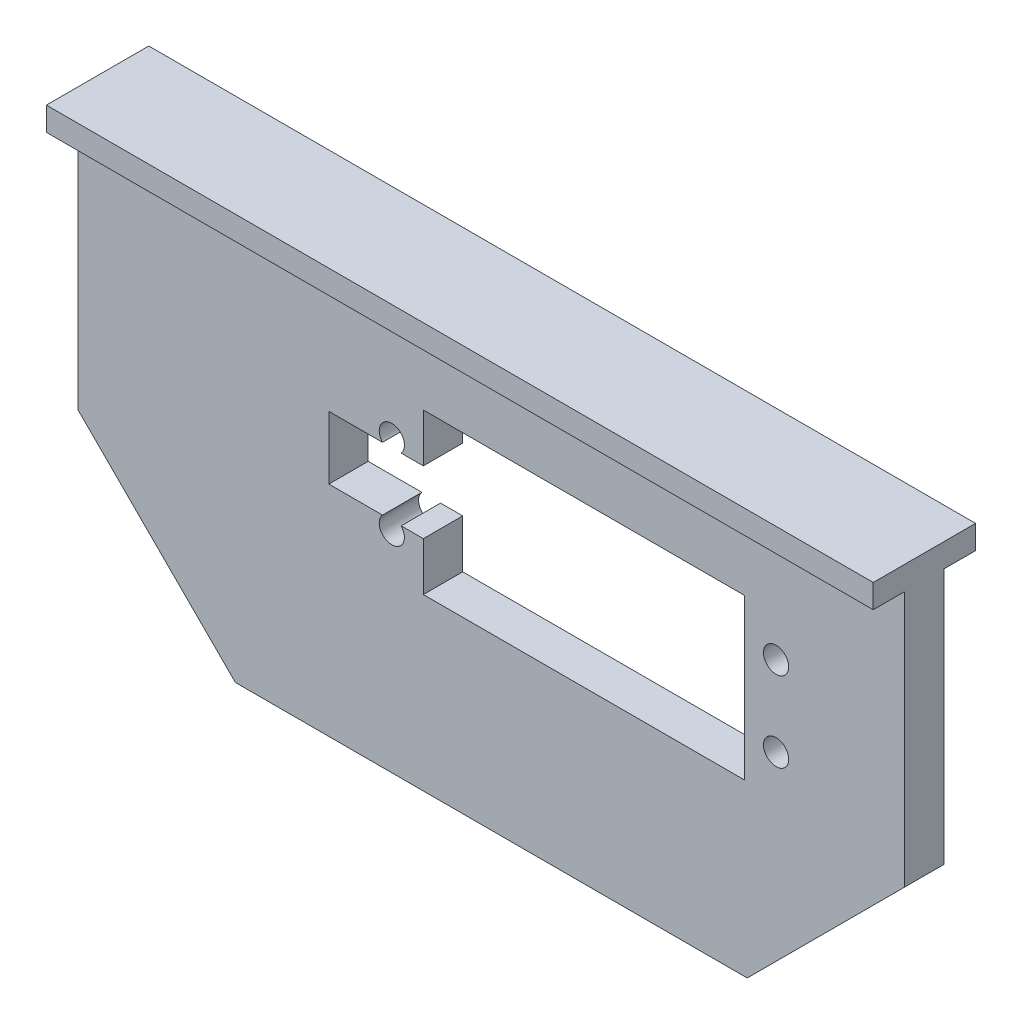
SolidWorks part; units mm, degrees
ref_plane "前视基准面" through (0, 0, 0) normal (0, 0, 1) x (1, 0, 0)
ref_plane "上视基准面" through (0, 0, 0) normal (0, 1, 0) x (1, 0, 0)
ref_plane "右视基准面" through (0, 0, 0) normal (1, 0, 0) x (0, 0, -1)
other "Configuration Table"
sketch "草图1" plane through (0, 0, 0) normal (0, 0, 1) x (1, 0, 0)
  line L2 (43.865, -10.5968) -> (84.665, -10.5968)
  line L3 (43.865, -10.5968) -> (43.865, -30.8968)
  line L4 (43.865, -30.8968) -> (84.665, -30.8968)
  line L5 (84.665, -10.5968) -> (84.665, -30.8968)
  line L6 (0, 0) -> (0, -52.5)
  line L7 (105, 0) -> (105, -52.5)
  line L8 (0, -52.5) -> (105, -52.5)
  line L9 (0, 0) -> (105, 0)
  circle A2 centre (39.865, -15.6718) radius 1.6
  circle A3 centre (39.865, -25.8218) radius 1.6
  circle A4 centre (88.665, -15.6718) radius 1.6
  circle A5 centre (88.665, -25.8218) radius 1.6
  dimension "D5" = 3.2
  dimension "D6" = 3.2
  dimension "D10" = 3.2
  dimension "D11" = 3.2
  dimension "D7" = 52.5
  dimension "D1" = 105
  dimension "D3" = 40.8
  dimension "D4" = 20.3
  dimension "D8" = 4
  dimension "D9" = 4
  dimension "D12" = 4
  dimension "D13" = 4
extrude "凸台-拉伸1" add sketch "草图1" along normal blind 5
sketch "草图3" plane through (0, 0, 0) normal (-1, 0, 0) x (0, 0, 1)
  line L0 (-4, 0) -> (9, 0)
  line L1 (5, 0) -> (5, -52.5) construction
  line L2 (9, 0) -> (9, 3)
  line L3 (9, 3) -> (-4, 3)
  line L4 (-4, 3) -> (-4, 0)
  point P3 (2.5, 0)
  dimension "D1" = 4
  dimension "D2" = 3
extrude "凸台-拉伸2" add sketch "草图3" against normal through all
sketch "草图4" plane through (0, 0, 5) normal (0, 0, 1) x (1, 0, 0)
  line L2 (43.865, -20.7468) -> (32.5545, -20.7468) construction
  line L9 (43.865, -10.5968) -> (43.865, -30.8968) construction
  line L11 (55.865, -24.7468) -> (31.865, -24.7468)
  line L12 (55.865, -24.7468) -> (55.865, -16.7468)
  line L13 (55.865, -16.7468) -> (31.865, -16.7468)
  line L14 (31.865, -24.7468) -> (31.865, -16.7468)
  line L15 (55.865, -24.7468) -> (31.865, -16.7468) construction
  line L16 (55.865, -16.7468) -> (31.865, -24.7468) construction
  dimension "D3" = 8
  dimension "D4" = 12
extrude "切除-拉伸1" cut sketch "草图4" against normal through all
chamfer "倒角1" distance 20 angle 45 2 edges at (105, -52.5, 2.5) (0, -52.5, 2.5)
